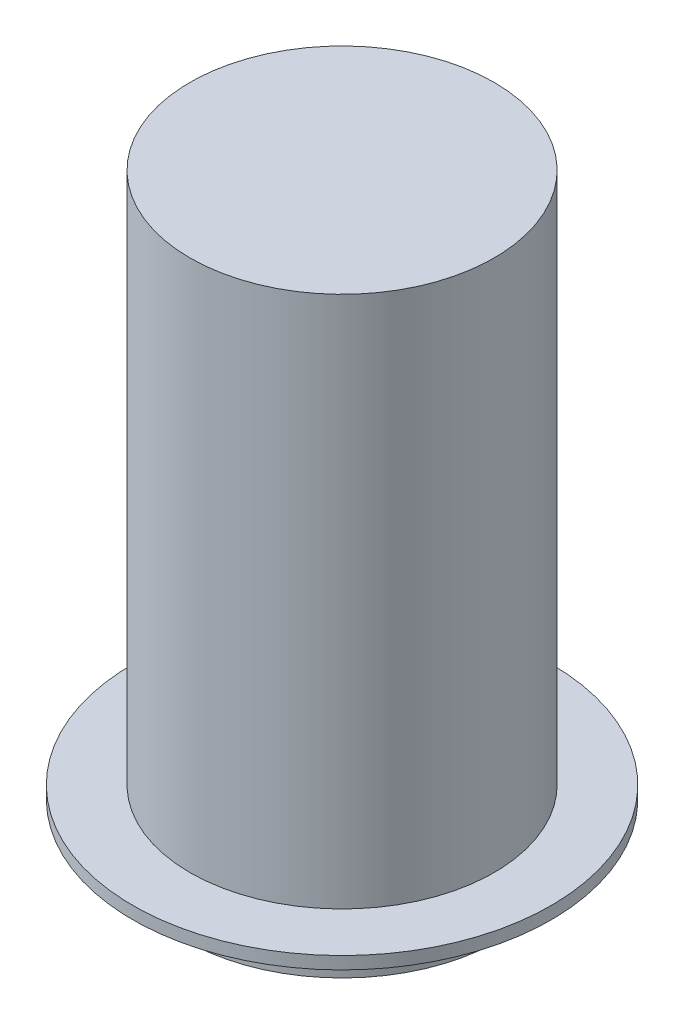
SolidWorks part; units mm, degrees
ref_plane "Front Plane" through (0, 0, 0) normal (0, 0, 1) x (1, 0, 0)
ref_plane "Top Plane" through (0, 0, 0) normal (0, 1, 0) x (1, 0, 0)
ref_plane "Right Plane" through (0, 0, 0) normal (1, 0, 0) x (0, 0, -1)
sketch "Sketch1" plane through (0, 0, 0) normal (0, 0, 1) x (1, 0, 0)
  line L0 (0, 0) -> (0, 39.2311) construction
  line L1 (0, 35.82) -> (10, 35.82)
  line L2 (10, 35.82) -> (10, 0.82)
  line L3 (10, 0.82) -> (13.75, 0.82)
  line L4 (13.75, 0.82) -> (13.75, 0)
  line L5 (13.75, 0) -> (10.325, 0)
  line L6 (10.325, 0) -> (10.325, -2.88)
  line L7 (10.325, -2.88) -> (2, -2.88)
  line L8 (2, -2.88) -> (2, -6.9948)
  line L9 (2, -6.9948) -> (0, -6.9948)
  line L10 (0, -6.9948) -> (0, 35.82)
  point P9 (6.4876, -17.2859)
  point P14 (6.7651, 0)
  point P15 (0, 39.2311)
  dimension "D1" = 20
  dimension "D2" = 35
  dimension "D3" = 0.82
  dimension "D4" = 38.7
  dimension "D5" = 20.65
  dimension "D6" = 27.5
  dimension "D7" = 4.1148
  dimension "D8" = 4
revolve "Revolve1" add sketch "Sketch1" angle 360 about L0
